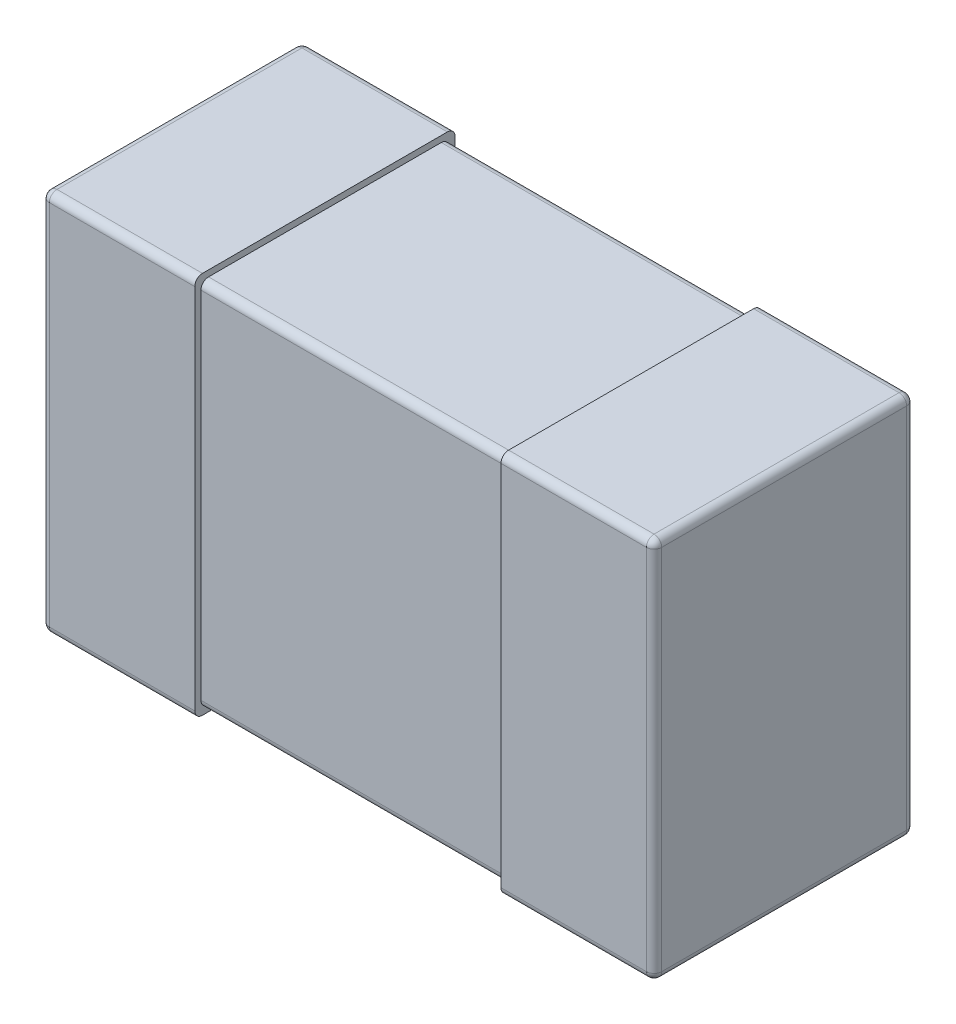
SolidWorks part; units mm, degrees
ref_plane "Спереди" through (0, 0, 0) normal (0, 0, 1) x (1, 0, 0)
ref_plane "Сверху" through (0, 0, 0) normal (0, 1, 0) x (1, 0, 0)
ref_plane "Справа" through (0, 0, 0) normal (1, 0, 0) x (0, 0, -1)
sketch "Эскиз3" plane through (0, 0, 0) normal (0, 0, 1) x (1, 0, 0)
  line L0 (0, 0.7005) -> (0, -0.7992) construction
  line L1 (1, 0.625) -> (1, -0.625)
  line L2 (1, 0.625) -> (0.5, 0.625)
  line L3 (0.5, 0.625) -> (0.5, -0.625)
  line L4 (1, -0.625) -> (0.5, -0.625)
  line L5 (-1, 0.625) -> (-0.5, 0.625)
  line L6 (-1, 0.625) -> (-1, -0.625)
  line L7 (-1, -0.625) -> (-0.5, -0.625)
  line L8 (-0.5, 0.625) -> (-0.5, -0.625)
  line L9 (-1, -0.625) -> (-0.5, 0.625) construction
  line L10 (-1, 0.625) -> (-0.5, -0.625) construction
  line L11 (0, 0) -> (-0.75, 0) construction
  point P11 (-0.75, 0)
  dimension "D1" = 0.5
  dimension "D2" = 1.25
  dimension "D3" = 2
extrude "Вытянуть3" add sketch "Эскиз3" along normal blind 0.85
sketch "Эскиз4" plane through (0, 0, 0) normal (0, 0, 1) x (1, 0, 0)
  line L1 (0.5, -0.605) -> (-0.5, -0.605)
  line L2 (0.5, -0.605) -> (0.5, 0.605)
  line L3 (0.5, 0.605) -> (-0.5, 0.605)
  line L4 (-0.5, -0.605) -> (-0.5, 0.605)
  line L5 (0.5, -0.605) -> (-0.5, 0.605) construction
  line L6 (0.5, 0.605) -> (-0.5, -0.605) construction
  line L7 (-0.5, -0.625) -> (-0.5, 0.625) construction
  point P0 (0, 0)
  dimension "D1" = 0.02
extrude "Бобышка-Вытянуть3" add sketch "Эскиз4" along normal offset from surface (0.81 mm away) 0.02 from offset 0.02 up to face at (-0.75, 0, 0.85)
fillet "Скругление2" radius 0.025 16 edges at (-1, 0.625, 0.425) (-1, 0, 0.85) (-1, -0.625, 0.425) (-1, 0, 0) (-0.75, 0.625, 0) (-0.75, -0.625, 0) (-0.75, 0.625, 0.85) (-0.75, -0.625, 0.85) (1, -0.625, 0.425) (1, 0, 0.85) (1, 0.625, 0.425) (1, 0, 0) (0.75, 0.625, 0) (0.75, 0.625, 0.85) (0.75, -0.625, 0.85) (0.75, -0.625, 0)
fillet "Скругление3" radius 0.025 4 edges at (0, -0.605, 0.02) (0, 0.605, 0.02) (0, 0.605, 0.83) (0, -0.605, 0.83)
